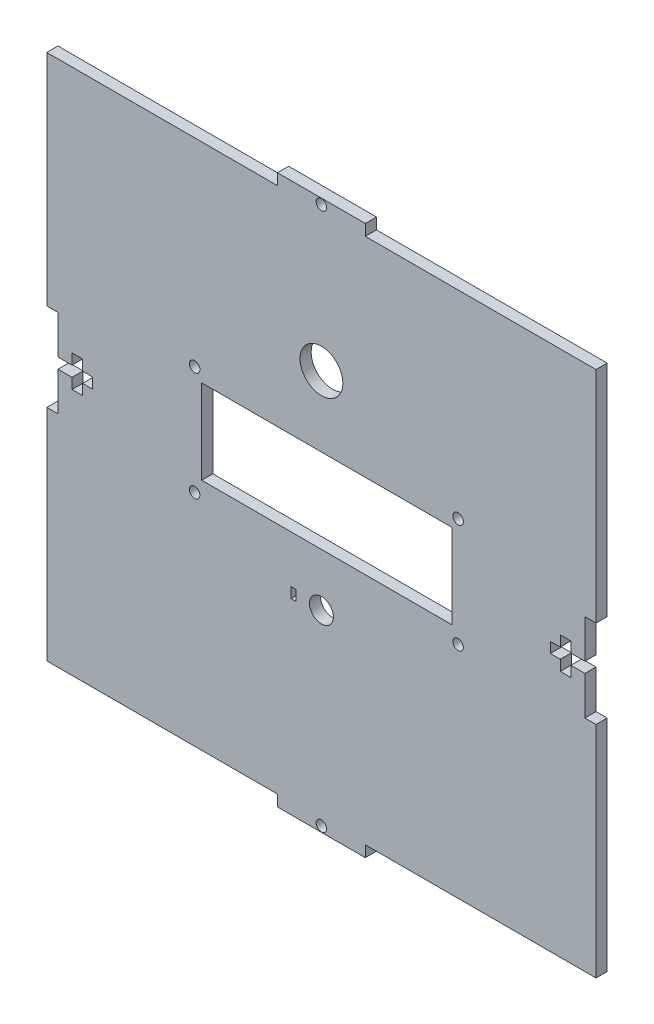
SolidWorks part; units mm, degrees
ref_plane "Front Plane" through (0, 0, 0) normal (0, 0, 1) x (1, 0, 0)
ref_plane "Top Plane" through (0, 0, 0) normal (0, 1, 0) x (1, 0, 0)
ref_plane "Right Plane" through (0, 0, 0) normal (1, 0, 0) x (0, 0, -1)
sketch "Sketch1" plane through (0, 0, 0) normal (0, 0, 1) x (1, 0, 0)
  line L0 (-12.5, 25) -> (12.5, 25) construction
  line L1 (-78.18, 75) -> (-12.5, 75)
  line L2 (-78.18, 75) -> (-78.18, 12.5)
  line L3 (-78.18, -75) -> (-12.5, -75)
  line L4 (78.18, 75) -> (78.18, 12.5)
  line L5 (-78.18, 75) -> (78.18, -75) construction
  line L6 (-78.18, -75) -> (78.18, 75) construction
  line L11 (12.5, 75) -> (12.5, 78.18)
  line L12 (12.5, 78.18) -> (-12.5, 78.18)
  line L17 (-12.5, 75) -> (-12.5, 78.18)
  line L18 (12.5, 75) -> (78.18, 75)
  line L25 (0, 100) -> (0, -75) construction
  line L26 (-100, 0) -> (100, 0) construction
  line L27 (-75, -1.5) -> (-75, -12.5)
  line L28 (-75, 12.5) -> (-78.18, 12.5)
  line L29 (-75, 12.5) -> (-75, 1.5)
  line L30 (-75, -12.5) -> (-78.18, -12.5)
  line L32 (-75, 12.5) -> (-78.18, -12.5) construction
  line L33 (-75, -12.5) -> (-78.18, 12.5) construction
  line L34 (-65.18, 1.5) -> (-68, 1.5)
  line L35 (-65.18, 1.5) -> (-65.18, -1.5)
  line L36 (-65.18, -1.5) -> (-68, -1.5)
  line L38 (-65.18, 1.5) -> (-75, -1.5) construction
  line L39 (-65.18, -1.5) -> (-75, 1.5) construction
  line L44 (-71, 4.5) -> (-68, 4.5)
  line L45 (-71, 4.5) -> (-71, 1.5)
  line L46 (-71, -4.5) -> (-68, -4.5)
  line L47 (-68, 4.5) -> (-68, 1.5)
  line L48 (-71, 4.5) -> (-68, -4.5) construction
  line L49 (-71, -4.5) -> (-68, 4.5) construction
  line L50 (-71, -1.5) -> (-71, -4.5)
  line L51 (-68, -1.5) -> (-68, -4.5)
  line L52 (-71, 1.5) -> (-75, 1.5)
  line L53 (-71, -1.5) -> (-75, -1.5)
  line L54 (65.18, 1.5) -> (68, 1.5)
  line L55 (68, 4.5) -> (68, 1.5)
  line L56 (71, 4.5) -> (68, 4.5)
  line L57 (71, 4.5) -> (71, 1.5)
  line L58 (71, 1.5) -> (75, 1.5)
  line L59 (75, 12.5) -> (75, 1.5)
  line L60 (75, 12.5) -> (78.18, 12.5)
  line L62 (75, -12.5) -> (78.18, -12.5)
  line L63 (75, -1.5) -> (75, -12.5)
  line L64 (71, -1.5) -> (75, -1.5)
  line L65 (71, -1.5) -> (71, -4.5)
  line L66 (71, -4.5) -> (68, -4.5)
  line L67 (68, -1.5) -> (68, -4.5)
  line L68 (65.18, -1.5) -> (68, -1.5)
  line L69 (65.18, 1.5) -> (65.18, -1.5)
  line L70 (-78.18, -12.5) -> (-78.18, -75)
  line L71 (78.18, -12.5) -> (78.18, -75)
  line L72 (0, -78.18) -> (0, -75) construction
  line L74 (12.5, -75) -> (12.5, -78.18)
  line L75 (12.5, -78.18) -> (-12.5, -78.18)
  line L76 (-12.5, -75) -> (-12.5, -78.18)
  line L77 (12.5, -76.59) -> (-12.5, -76.59) construction
  line L78 (12.5, -75) -> (78.18, -75)
  circle A2 centre (0, -76.59) radius 1.5
  circle A3 centre (0, 76.59) radius 1.5
  point P0 (0, 0)
  point P6 (-50, 50)
  point P11 (50, 50)
  point P16 (0, 0)
  point P27 (0, 25)
  point P30 (-76.59, 0)
  point P35 (-70.09, 0)
  point P40 (-70.09, 0)
  point P41 (-69.5, 0)
  dimension "D13" = 25
  dimension "D23" = 3
  dimension "D1" = 150
  dimension "D2" = 156.36
  dimension "D3" = 9
  dimension "D9" = 50
  dimension "D10" = 50
  dimension "D14" = 50
  dimension "D15" = 25
  dimension "D16" = 13
  dimension "D17" = 3.18
  dimension "D18" = 3
  dimension "D19" = 4
  dimension "D20" = 3
  dimension "D21" = 3.18
  dimension "D22" = 25
extrude "Boss-Extrude1" add sketch "Sketch1" along normal blind 3.18
sketch "Sketch5" plane through (0, 0, 3.18) normal (0, 0, 1) x (1, 0, 0)
  line L0 (-78.18, -75) -> (-12.5, -75) construction
  line L1 (-59.4516, -75) -> (-39.4516, -75)
  line L2 (-59.4516, -75) -> (-59.4516, -55)
  line L3 (-59.4516, -55) -> (-39.4516, -55)
  line L4 (-39.4516, -75) -> (-39.4516, -55)
  dimension "D1" = 20
  dimension "D2" = 20
sketch "Sketch6" plane through (0, 0, 3.18) normal (0, 0, 1) x (1, 0, 0)
  line L0 (-34.0945, 14.7318) -> (-34.0945, 15.794) construction
  line L1 (-33.2445, 15.5818) -> (-34.2717, 15.5818) construction
  line L2 (36.2555, -8.4182) -> (37.1221, -8.4182) construction
  line L3 (37.1055, -7.5682) -> (37.1055, -8.6069) construction
  line L5 (-34.0945, 15.5818) -> (37.1055, 15.5818)
  line L6 (-34.0945, 15.5818) -> (-34.0945, -8.4182)
  line L7 (-34.0945, -8.4182) -> (37.1055, -8.4182)
  line L8 (37.1055, 15.5818) -> (37.1055, -8.4182)
  circle A0 centre (-36.0945, 18.5818) radius 1.5
  circle A1 centre (-36.0945, -12.4182) radius 1.5
  circle A2 centre (38.9055, -12.4182) radius 1.5
  circle A3 centre (38.9055, 18.5818) radius 1.5
  dimension "D1" = 3
  dimension "D2" = 3
  dimension "D3" = 3
  dimension "D4" = 3
extrude "Cut-Extrude2" cut sketch "Sketch6" against normal blind 10
sketch "Sketch7" plane through (0, 0, 3.18) normal (0, 0, 1) x (1, 0, 0)
  line L0 (0, 78.18) -> (0, -78.18) construction
  line L1 (12.5, 78.18) -> (-12.5, 78.18) construction
  line L2 (-12.5, -78.18) -> (12.5, -78.18) construction
  line L3 (36.2555, -8.4182) -> (-33.2445, -8.4182) construction
  circle A0 centre (0, -23.4182) radius 3.4
  dimension "D1" = 6.8
  dimension "D2" = 15
extrude "Cut-Extrude3" cut sketch "Sketch7" against normal blind 10
sketch "Sketch8" plane through (0, 0, 3.18) normal (0, 0, 1) x (1, 0, 0)
  line L0 (0, 78.18) -> (0, -78.18) construction
  line L1 (12.5, 78.18) -> (-12.5, 78.18) construction
  line L2 (-12.5, -78.18) -> (12.5, -78.18) construction
  line L3 (37.1055, 15.5818) -> (-34.0945, 15.5818) construction
  circle A0 centre (0, 35.5818) radius 6.1
  dimension "D1" = 12.2
  dimension "D2" = 20
extrude "Cut-Extrude4" cut sketch "Sketch8" against normal blind 10
sketch "Sketch9" plane through (0, 0, 3.18) normal (0, 0, 1) x (1, 0, 0)
  line L1 (-8.6427, -21.9166) -> (-7.2829, -21.9166)
  line L2 (-8.6427, -21.9166) -> (-8.6427, -24.8717)
  line L3 (-8.6427, -24.8717) -> (-7.2829, -24.8717)
  line L4 (-7.2829, -21.9166) -> (-7.2829, -24.8717)
extrude "Cut-Extrude5" cut sketch "Sketch9" against normal blind 10
